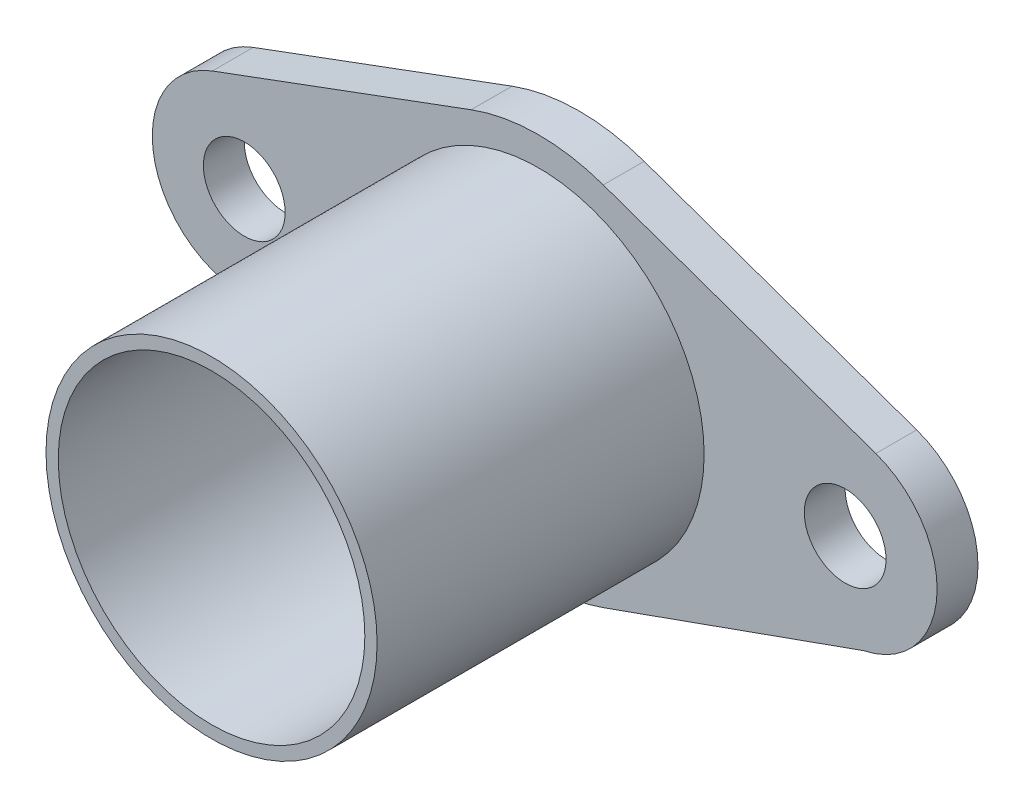
SolidWorks part; units mm, degrees
ref_plane "Front Plane" through (0, 0, 0) normal (0, 0, 1) x (1, 0, 0)
ref_plane "Top Plane" through (0, 0, 0) normal (0, 1, 0) x (1, 0, 0)
ref_plane "Right Plane" through (0, 0, 0) normal (1, 0, 0) x (0, 0, -1)
sketch "Sketch1" plane through (0, 0, 0) normal (0, 0, 1) x (1, 0, 0)
  line L0 (-79.8125, 21.1001) -> (-16.4931, 44.5447)
  line L1 (-79.8125, -21.1001) -> (-16.4931, -44.5447)
  line L2 (15.9704, -44.7347) -> (79.56, -22.0331)
  line L3 (15.8333, 44.7834) -> (82.5, 21.2132)
  circle A0 centre (0, 0) radius 37.5
  arc A1 (-16.4931, -44.5447) -> (15.9704, -44.7347) centre (0, 0) ccw
  circle A2 centre (-72, 0) radius 10
  circle A3 centre (75, 0) radius 10
  arc A4 (-79.8125, 21.1001) -> (-79.8125, -21.1001) centre (-72, 0) ccw
  arc A5 (79.56, -22.0331) -> (82.5, 21.2132) centre (75, 0) ccw
  arc A6 (15.8333, 44.7834) -> (-16.4931, 44.5447) centre (0, 0) ccw
  dimension "D1" = 75
  dimension "D2" = 20
  dimension "D3" = 72
  dimension "D5" = 45
  dimension "D7" = 95
  dimension "D4" = 75
extrude "Boss-Extrude1" add sketch "Sketch1" along normal blind 10
sketch "Sketch2" plane through (0, 0, 10) normal (0, 0, 1) x (1, 0, 0)
  circle A0 centre (0, 0) radius 40.5
  circle A1 centre (0, 0) radius 37.5 construction
  circle A2 centre (0, 0) radius 37.5
  dimension "D1" = 3
extrude "Boss-Extrude2" add sketch "Sketch2" along normal blind 80
